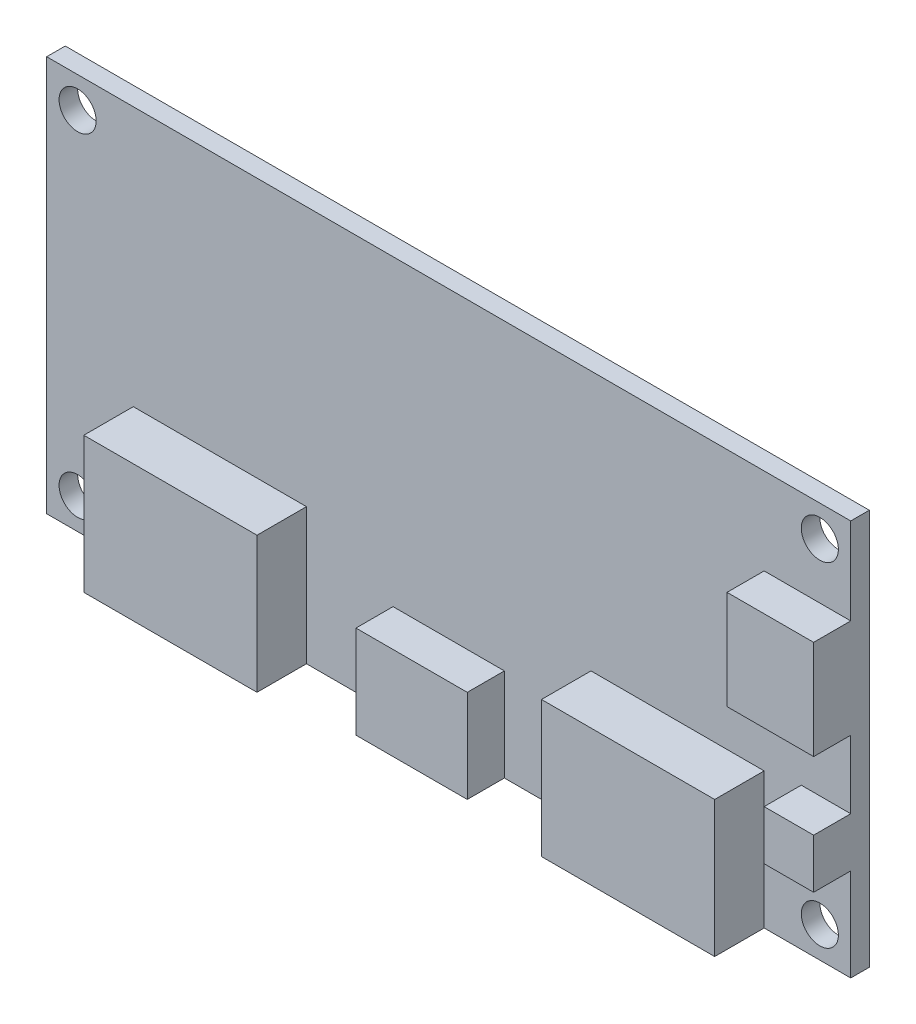
SolidWorks part; units mm, degrees
ref_plane "Front Plane" through (0, 0, 0) normal (0, 0, 1) x (1, 0, 0)
ref_plane "Top Plane" through (0, 0, 0) normal (0, 1, 0) x (1, 0, 0)
ref_plane "Right Plane" through (0, 0, 0) normal (1, 0, 0) x (0, 0, -1)
sketch "Sketch1" plane through (0, 0, 0) normal (0, 0, 1) x (1, 0, 0)
  line L1 (0, 0) -> (65, 0)
  line L2 (0, 0) -> (0, 32)
  line L3 (0, 32) -> (65, 32)
  line L4 (65, 0) -> (65, 32)
  circle A0 centre (2.5, 2.5) radius 1.5
  circle A1 centre (2.5, 29.5) radius 1.5
  circle A2 centre (62.5, 29.5) radius 1.5
  circle A3 centre (62.5, 2.5) radius 1.5
  point P13 (0, 0)
  point P14 (0, 0)
  point P15 (0, 0)
  point P16 (0, 0)
  point P17 (0, 0)
  point P18 (50.659, 2.5)
  dimension "D3" = 3
  dimension "D1" = 65
  dimension "D2" = 32
  dimension "D4" = 2.5
  dimension "D5" = 2.5
  dimension "D6" = 2.5
  dimension "D7" = 2.5
extrude "Boss-Extrude1" add sketch "Sketch1" along normal blind 1.5
sketch "Sketch2" plane through (0, 0, 1.5) normal (0, 0, 1) x (1, 0, 0)
  line L0 (0, 0) -> (65, 0) construction
  line L1 (7, 11) -> (21, 11)
  line L2 (7, 11) -> (7, 0)
  line L3 (7, 0) -> (21, 0)
  line L4 (21, 11) -> (21, 0)
  line L5 (32.5, 32) -> (32.5, 0) construction
  line L6 (44, 11) -> (58, 11)
  line L7 (44, 11) -> (44, 0)
  line L8 (44, 0) -> (58, 0)
  line L9 (58, 11) -> (58, 0)
  line L10 (65, 32) -> (0, 32) construction
  dimension "D1" = 11
  dimension "D2" = 11
  dimension "D3" = 14
  dimension "D4" = 14
  dimension "D5" = 23
extrude "Boss-Extrude2" add sketch "Sketch2" along normal blind 4
sketch "Sketch3" plane through (0, 0, 1.5) normal (0, 0, 1) x (1, 0, 0)
  line L0 (65, 0) -> (65, 32) construction
  line L1 (58, 25) -> (65, 25)
  line L2 (58, 25) -> (58, 17)
  line L3 (58, 17) -> (65, 17)
  line L4 (65, 25) -> (65, 17)
  line L5 (21, 0) -> (44, 0) construction
  line L6 (61, 11.5) -> (65, 11.5)
  line L7 (61, 11.5) -> (61, 7.5)
  line L8 (61, 7.5) -> (65, 7.5)
  line L9 (65, 11.5) -> (65, 7.5)
  line L10 (28, 7.5) -> (37, 7.5)
  line L11 (28, 7.5) -> (28, 0)
  line L12 (28, 0) -> (37, 0)
  line L13 (37, 7.5) -> (37, 0)
  line L14 (32.5, 32) -> (32.5, 0) construction
  line L15 (65, 32) -> (0, 32) construction
  line L16 (58, 0) -> (65, 0) construction
  dimension "D1" = 7
  dimension "D2" = 4
  dimension "D3" = 4
  dimension "D4" = 8
  dimension "D5" = 9
  dimension "D6" = 7.5
  dimension "D7" = 17
  dimension "D8" = 7.5
extrude "Boss-Extrude3" add sketch "Sketch3" along normal blind 3
